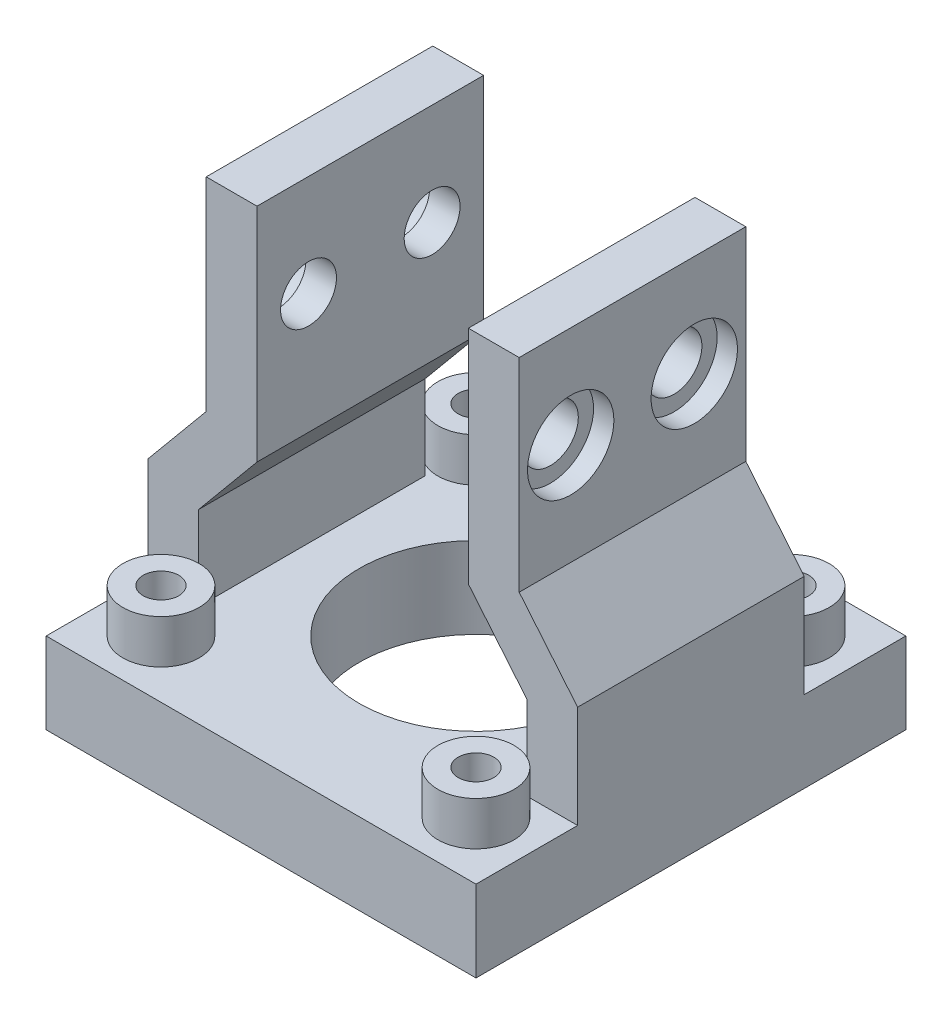
SolidWorks part; units mm, degrees
ref_plane "Front Plane" through (0, 0, 0) normal (0, 0, 1) x (1, 0, 0)
ref_plane "Top Plane" through (0, 0, 0) normal (0, 1, 0) x (1, 0, 0)
ref_plane "Right Plane" through (0, 0, 0) normal (1, 0, 0) x (0, 0, -1)
sketch "Sketch1" plane through (0, 0, 0) normal (0, 1, 0) x (1, 0, 0)
  line L0 (0, 28.2567) -> (0, -33.0091) construction
  line L1 (-21.15, 21.15) -> (21.15, 21.15)
  line L2 (-21.15, 21.15) -> (-21.15, -21.15)
  line L3 (-21.15, -21.15) -> (21.15, -21.15)
  line L4 (21.15, 21.15) -> (21.15, -21.15)
  line L5 (-21.15, 21.15) -> (21.15, -21.15) construction
  line L6 (-21.15, -21.15) -> (21.15, 21.15) construction
  line L7 (-28.1424, 0) -> (28.0711, 0) construction
  line L12 (-15.5, 15.5) -> (15.5, -15.5) construction
  line L13 (-15.5, -15.5) -> (15.5, 15.5) construction
  circle A1 centre (-15.5, 15.5) radius 1.75
  circle A2 centre (15.5, 15.5) radius 1.75
  circle A3 centre (15.5, -15.5) radius 1.75
  circle A4 centre (-15.5, -15.5) radius 1.75
  circle A5 centre (0, 0) radius 11.5
  point P0 (0, 0)
  point P6 (0, 0)
  dimension "D3" = 31
  dimension "D5" = 3.5
  dimension "D6" = 23
  dimension "D1" = 42.3
  dimension "D2" = 42.3
  dimension "D4" = 31
extrude "Boss-Extrude1" add sketch "Sketch1" along normal blind 8
sketch "Sketch3" plane through (0, 0, 21.15) normal (0, 0, 1) x (1, 0, 0)
  line L0 (-21.15, 8) -> (-21.15, 18.0805)
  line L5 (-21.15, 18.0805) -> (-15.4, 25.0041)
  line L6 (-15.4, 25.0041) -> (-15.4, 45.0041)
  line L7 (-15.4, 45.0041) -> (-10.4, 45.0041)
  line L8 (-10.4, 45.0041) -> (-10.4, 23.1987)
  line L9 (-10.4, 23.1987) -> (-16.15, 16.275)
  line L10 (-16.15, 16.275) -> (-16.15, 8)
  line L11 (-21.15, 8) -> (21.15, 8) construction
  line L12 (0, 0) -> (0, 39.89) construction
  line L13 (-21.15, 0) -> (21.15, 0) construction
  line L14 (16.15, 16.275) -> (16.15, 8)
  line L15 (10.4, 23.1987) -> (16.15, 16.275)
  line L16 (10.4, 45.0041) -> (10.4, 23.1987)
  line L17 (15.4, 45.0041) -> (10.4, 45.0041)
  line L18 (15.4, 25.0041) -> (15.4, 45.0041)
  line L19 (21.15, 18.0805) -> (15.4, 25.0041)
  line L20 (21.15, 8) -> (21.15, 18.0805)
  line L21 (-21.15, 8) -> (-16.15, 8)
  line L22 (16.15, 8) -> (21.15, 8)
  dimension "D1" = 5
  dimension "D2" = 5
  dimension "D3" = 5
  dimension "D4" = 20.8
  dimension "D5" = 9
  dimension "D6" = 20
extrude "Boss-Extrude2" add sketch "Sketch3" against normal blind 22.3 from offset 10 offset against normal yes
sketch "Sketch4" plane through (-15.4, 0, 0) normal (-1, 0, 0) x (0, 0, 1)
  line L0 (0, 37.5869) -> (0, -1.5289) construction
  line L2 (-11.15, 45.0041) -> (11.15, 45.0041) construction
  circle A0 centre (-6.081, 35.0041) radius 2.75
  circle A1 centre (6.081, 35.0041) radius 2.75
  dimension "D1" = 5.5
  dimension "10" = 10
extrude "Cut-Extrude1" cut sketch "Sketch4" against normal through all
sketch "Sketch5" plane through (0, 8, 0) normal (0, 1, 0) x (1, 0, 0)
  line L0 (0, 22.5499) -> (0, -23.4813) construction
  line L1 (-28.5322, 0) -> (29.177, 0) construction
  circle A0 centre (-15.5, 15.5) radius 1.75
  circle A2 centre (-15.5, 15.5) radius 3.75
  circle A3 centre (15.5, 15.5) radius 1.75
  circle A4 centre (15.5, 15.5) radius 3.75
  circle A5 centre (15.5, -15.5) radius 1.75
  circle A6 centre (15.5, -15.5) radius 3.75
  circle A7 centre (-15.5, -15.5) radius 3.75
  circle A8 centre (-15.5, -15.5) radius 1.75
  dimension "D1" = 2
extrude "Boss-Extrude3" add sketch "Sketch5" along normal blind 4.3 contours A5 | A6 | A4 | A3 | A0 | A2 | A7 | A8
sketch "Sketch7" plane through (-15.4, 0, 0) normal (-1, 0, 0) x (0, 0, 1)
  circle A0 centre (-6.081, 35.0041) radius 4.25
  circle A1 centre (6.081, 35.0041) radius 4.25
  dimension "D1" = 8.5
extrude "Cut-Extrude2" cut sketch "Sketch7" against normal blind 2
sketch "Sketch8" plane through (15.4, 0, 0) normal (1, 0, 0) x (0, 0, -1)
  circle A0 centre (-6.081, 35.0041) radius 4.25 construction
  circle A1 centre (-6.081, 35.0041) radius 4.25
  circle A2 centre (6.081, 35.0041) radius 4.25 construction
  circle A3 centre (6.081, 35.0041) radius 4.25
extrude "Cut-Extrude3" cut sketch "Sketch8" against normal blind 2
